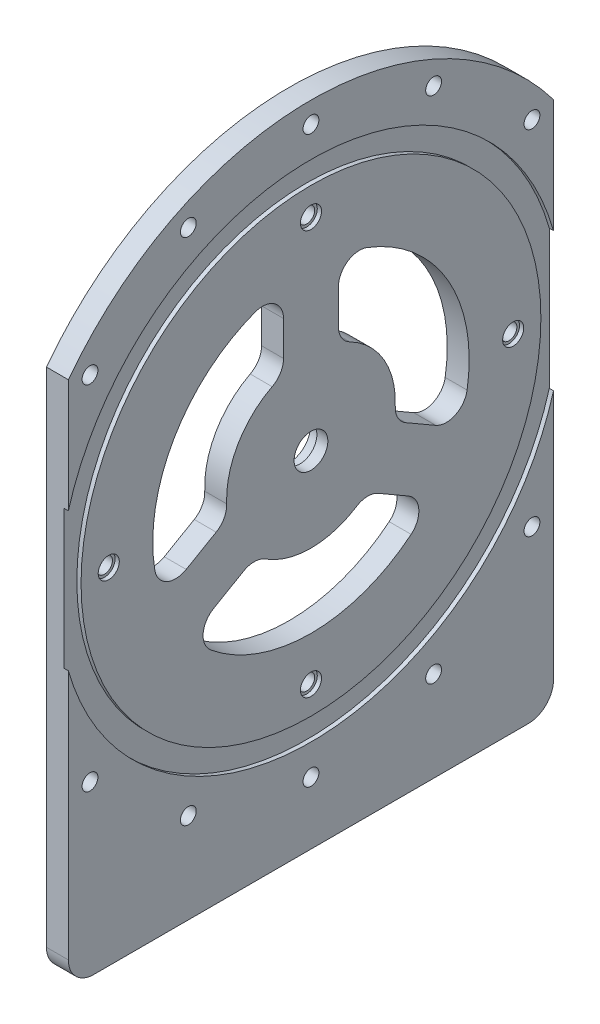
SolidWorks part; units mm, degrees
material "6061 Alloy"
ref_plane "Front Plane" through (0, 0, 0) normal (0, 0, 1) x (1, 0, 0)
ref_plane "Top Plane" through (0, 0, 0) normal (0, 1, 0) x (1, 0, 0)
ref_plane "Right Plane" through (0, 0, 0) normal (1, 0, 0) x (0, 0, -1)
sketch "Sketch1" plane through (0, 0, 0) normal (1, 0, 0) x (0, 0, -1)
  line L0 (0, -1000) -> (0, 49000) construction
  line L1 (5.5562, 0) -> (2.7781, 4.8119) construction
  line L2 (2.7781, 4.8119) -> (-2.7781, 4.8119) construction
  line L3 (-2.7781, 4.8119) -> (-5.5562, 0) construction
  line L4 (-5.5562, 0) -> (-2.7781, -4.8119) construction
  line L5 (-2.7781, -4.8119) -> (2.7781, -4.8119) construction
  line L6 (2.7781, -4.8119) -> (5.5562, 0) construction
  line L7 (-65.405, -103.8551) -> (65.405, -103.8551)
  line L8 (-73.025, -96.2351) -> (-73.025, -69.997)
  line L10 (73.025, -96.2351) -> (73.025, -69.997)
  circle A0 centre (0, 0) radius 69.85 construction
  circle A1 centre (0, 0) radius 76.2 construction
  circle A2 centre (0, 0) radius 5.08
  circle A3 centre (0, 0) radius 3.9688 construction
  arc A4 (79.6018, -44.9981) -> (-79.6018, -44.9981) centre (0, 0) ccw
  circle A5 centre (0, 0) radius 11.5094 construction
  circle A6 centre (0, 0) radius 91.44 construction
  arc A7 (65.405, -103.8551) -> (73.025, -96.2351) centre (65.405, -96.2351) ccw
  arc A8 (-65.405, -103.8551) -> (-73.025, -96.2351) centre (-65.405, -96.2351) cw
  arc A9 (79.6018, -44.9981) -> (73.025, -69.997) centre (123.825, -69.997) ccw
  arc A10 (-73.025, -69.997) -> (-79.6018, -44.9981) centre (-123.825, -69.997) ccw
  point P19 (73.025, -103.8551)
  point P26 (-73.025, -103.8551)
  dimension "D1" = 152.4
  dimension "D2" = 139.7
  dimension "D3" = 10.16
  dimension "D4" = 7.9375
  dimension "D5" = 15.24
  dimension "D6" = 23.0188
  dimension "D8" = 7.62
  dimension "D9" = 50.8
  dimension "D7" = 146.05
extrude "Boss-Extrude1" add sketch "Sketch1" along normal blind 6.604
sketch "Sketch2" plane through (0, 0, 0) normal (1, 0, 0) x (0, 0, -1)
  circle A0 centre (0, 0) radius 6.35 construction
  circle A1 centre (0, 0) radius 6.477
  dimension "D1" = 12.7
  dimension "D2" = 12.954
extrude "Cut-Extrude1" cut sketch "Sketch2" along direction (1, 0, 0) on the side of the normal blind 3.302
sketch "Sketch3" plane through (6.604, 0, 0) normal (1, 0, 0) x (0, 0, -1)
  circle A0 centre (0, 0) radius 75.946
  circle A1 centre (0, 0) radius 69.215
  dimension "D2" = 138.43
  dimension "D1" = 6.731
extrude "Cut-Extrude2" cut sketch "Sketch3" against normal blind 1.27
sketch "Sketch4" plane through (0, 0, 0) normal (-1, 0, 0) x (0, 0, 1)
  line L0 (0, -1000) -> (0, 49000) construction
  line L1 (-1000, 0) -> (49000, 0) construction
  circle A0 centre (-66.526, 53.0527) radius 2.3813
  circle A1 centre (0, 85.09) radius 2.3812
  circle A2 centre (-36.9192, 76.6634) radius 2.3812
  circle A3 centre (0, 0) radius 85.09 construction
  circle A4 centre (36.9192, 76.6634) radius 2.3812
  circle A5 centre (66.526, 53.0527) radius 2.3813
  circle A6 centre (82.9566, 18.9343) radius 2.3813
  circle A7 centre (82.9566, -18.9343) radius 2.3813
  circle A8 centre (66.526, -53.0527) radius 2.3812
  circle A9 centre (36.9192, -76.6634) radius 2.3813
  circle A10 centre (0, -85.09) radius 2.3812
  circle A11 centre (-36.9192, -76.6634) radius 2.3813
  circle A12 centre (-66.526, -53.0527) radius 2.3813
  circle A13 centre (-82.9566, -18.9343) radius 2.3813
  circle A14 centre (-82.9566, 18.9343) radius 2.3812
  point P34 (0, 0)
  dimension "D2" = 14
extrude "Cut-Extrude3" cut sketch "Sketch4" against normal through all
sketch "Sketch5" plane through (0, 0, 0) normal (-1, 0, 0) x (0, 0, 1)
  circle A0 centre (0, 85.09) radius 3.7783
  circle A1 centre (-82.9566, 18.9343) radius 3.7783
  circle A2 centre (-66.526, 53.0527) radius 3.7783
  circle A3 centre (36.9192, 76.6634) radius 3.7783
  circle A5 centre (-36.9192, 76.6634) radius 3.7783
  circle A6 centre (66.526, 53.0527) radius 3.7783
  circle A7 centre (82.9566, 18.9343) radius 3.7783
  circle A8 centre (82.9566, -18.9343) radius 3.7783
  circle A9 centre (66.526, -53.0527) radius 3.7783
  circle A10 centre (36.9192, -76.6634) radius 3.7783
  circle A11 centre (0, -85.09) radius 3.7783
  circle A12 centre (-36.9192, -76.6634) radius 3.7783
  circle A13 centre (-66.526, -53.0527) radius 3.7783
  circle A14 centre (-82.9566, -18.9343) radius 3.7783
  point P29 (0, 0)
  dimension "D1" = 14
extrude "Cut-Extrude4" cut sketch "Sketch5" against normal blind 1.27
sketch "Sketch6" plane through (0, 0, 0) normal (-1, 0, 0) x (0, 0, 1)
  line L0 (-1000, 0) -> (49000, 0) construction
  line L1 (0, 0) -> (25000, 43301.2702) construction
  line L2 (0, 0) -> (25000, -43301.2702) construction
  circle A0 centre (0, 0) radius 25.4 construction
  circle A1 centre (-19.0117, 0) radius 2.3813
  circle A2 centre (-9.5059, 16.4647) radius 2.3813
  circle A3 centre (9.5059, 16.4647) radius 2.3812
  circle A4 centre (19.0117, 0) radius 2.3813
  circle A5 centre (9.5059, -16.4647) radius 2.3813
  circle A6 centre (-9.5059, -16.4647) radius 2.3813
  point P19 (0, 0)
  dimension "D1" = 6
  dimension "D2" = 50.8
  dimension "D3" = 4.7625
  dimension "D4" = 19.0117
sketch "Sketch9" plane through (0, 0, 0) normal (-1, 0, 0) x (0, 0, 1)
  line L0 (0, 0) -> (0, 138.31) construction
  line L1 (0, 0) -> (103.2188, -59.5934) construction
  line L2 (0, 0) -> (-103.0172, -59.477) construction
  line L5 (-8.255, 38.6047) -> (-8.255, 28.1914)
  line L7 (8.255, 38.6047) -> (8.255, 28.1914)
  line L8 (37.5601, -12.1533) -> (28.542, -6.9467)
  line L10 (29.3051, -26.4514) -> (20.287, -21.2448)
  line L12 (-29.3051, -26.4514) -> (-20.287, -21.2448)
  line L14 (-37.5601, -12.1533) -> (-28.542, -6.9467)
  arc A0 (-8.255, 24.0211) -> (-24.9304, -4.8615) centre (0, 0) ccw construction
  arc A1 (-16.8519, 44.5438) -> (-47.0021, -7.6777) centre (0, 0) ccw
  arc A2 (-11.684, 22.5531) -> (-25.3736, -1.1579) centre (0, 0) ccw
  arc A3 (24.9304, -4.8615) -> (8.255, 24.0211) centre (0, 0) ccw construction
  arc A4 (25.3736, -1.1579) -> (11.684, 22.5531) centre (0, 0) ccw
  arc A5 (47.0021, -7.6777) -> (16.8519, 44.5438) centre (0, 0) ccw
  arc A6 (-16.6754, -19.1596) -> (16.6754, -19.1596) centre (0, 0) ccw construction
  arc A7 (-13.6896, -21.3952) -> (13.6896, -21.3952) centre (0, 0) ccw
  arc A8 (-30.1501, -36.8661) -> (30.1501, -36.8661) centre (0, 0) ccw
  arc A9 (-16.8519, 44.5438) -> (-8.255, 38.6047) centre (-14.605, 38.6047) cw
  arc A10 (-8.255, 28.1914) -> (-11.684, 22.5531) centre (-14.605, 28.1914) cw
  arc A11 (-25.3736, -1.1579) -> (-28.542, -6.9467) centre (-31.717, -1.4474) cw
  arc A12 (-47.0021, -7.6777) -> (-37.5601, -12.1533) centre (-40.7351, -6.654) ccw
  arc A13 (-30.1501, -36.8661) -> (-29.3051, -26.4514) centre (-26.1301, -31.9506) cw
  arc A14 (-20.287, -21.2448) -> (-13.6896, -21.3952) centre (-17.112, -26.744) cw
  arc A15 (13.6896, -21.3952) -> (20.287, -21.2448) centre (17.112, -26.744) cw
  arc A16 (30.1501, -36.8661) -> (29.3051, -26.4514) centre (26.1301, -31.9506) ccw
  arc A17 (47.0021, -7.6777) -> (37.5601, -12.1533) centre (40.7351, -6.654) cw
  arc A18 (28.542, -6.9467) -> (25.3736, -1.1579) centre (31.717, -1.4474) cw
  arc A19 (16.8519, 44.5438) -> (8.255, 38.6047) centre (14.605, 38.6047) ccw
  arc A20 (11.684, 22.5531) -> (8.255, 28.1914) centre (14.605, 28.1914) cw
  point P24 (0, 0)
  dimension "D1" = 120
  dimension "D3" = 95.25
  dimension "D4" = 50.8
  dimension "D7" = 6.35
  dimension "D2" = 120
  dimension "D5" = 16.51
  dimension "D6" = 3
extrude "Cut-Extrude5" cut sketch "Sketch9" against normal through all
sketch "Sketch10" plane through (0, 0, 0) normal (-1, 0, 0) x (0, 0, 1)
  circle A0 centre (0, 0) radius 50.8
  circle A1 centre (0, 0) radius 57.15
extrude "Cut-Extrude6" cut sketch "Sketch10" against normal blind 1.27
sketch "Sketch12" plane through (0, 0, 0) normal (-1, 0, 0) x (0, 0, 1)
  circle A0 centre (0, 60.8743) radius 2.3813
  circle A1 centre (60.8743, 0) radius 2.3813
  circle A2 centre (0, -60.8743) radius 2.3813
  circle A3 centre (-60.8743, 0) radius 2.3813
  point P13 (0, 0)
  point P33 (0, 0)
  dimension "D1" = 4
extrude "Cut-Extrude7" cut sketch "Sketch12" against normal through all
sketch "Sketch15" plane through (6.604, 0, 0) normal (1, 0, 0) x (0, 0, -1)
  circle A0 centre (0, 60.8743) radius 3.175
  circle A1 centre (60.8743, 0) radius 3.175
  circle A2 centre (0, -60.8743) radius 3.175
  circle A3 centre (-60.8743, 0) radius 3.175
  point P12 (0, 0)
  dimension "D1" = 4
extrude "Cut-Extrude11" cut sketch "Sketch15" against normal blind 1.27
sketch "Sketch16" plane through (0, 0, 0) normal (-1, 0, 0) x (0, 0, 1)
  line L0 (-73.025, -69.997) -> (-73.025, 55.0329)
  line L1 (-73.025, 55.0329) -> (-105.2318, 55.0329)
  line L2 (-105.2318, 55.0329) -> (-105.2318, -69.997)
  line L3 (-105.2318, -69.997) -> (-73.025, -69.997)
  line L4 (73.025, -69.997) -> (73.025, 55.0329)
  line L5 (73.025, 55.0329) -> (107.9275, 55.0329)
  line L6 (107.9275, 55.0329) -> (107.9275, -69.997)
  line L7 (107.9275, -69.997) -> (73.025, -69.997)
  arc A0 (79.6018, -44.9981) -> (-79.6018, -44.9981) centre (0, 0) ccw construction
extrude "Cut-Extrude12" cut sketch "Sketch16" against normal through all
